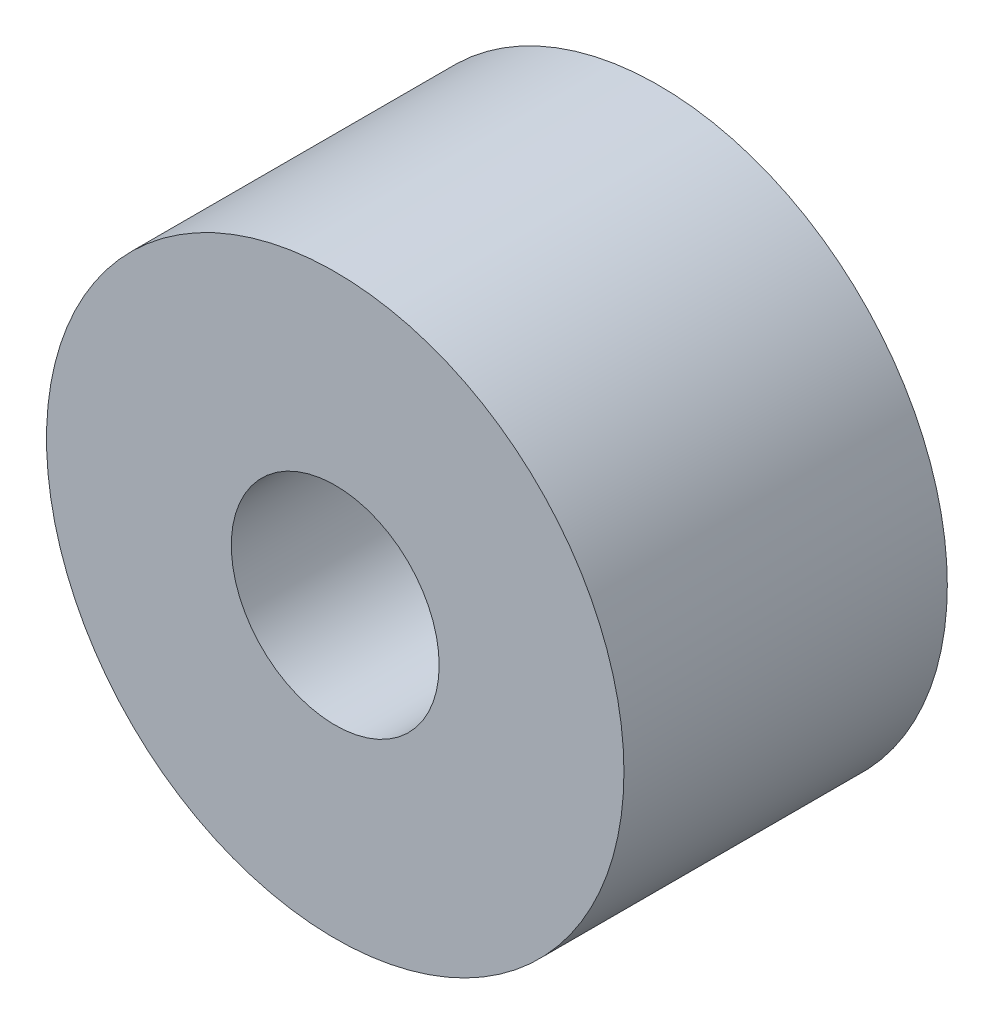
SolidWorks part; units mm, degrees
ref_plane "Plano frontal" through (0, 0, 0) normal (0, 0, 1) x (1, 0, 0)
ref_plane "Plano superior" through (0, 0, 0) normal (0, 1, 0) x (1, 0, 0)
ref_plane "Plano direito" through (0, 0, 0) normal (1, 0, 0) x (0, 0, -1)
sketch "Esboço1" plane through (0, 0, 0) normal (0, 0, 1) x (1, 0, 0)
  circle A0 centre (0, 0) radius 12.5
  circle A1 centre (0, 0) radius 4.5
  dimension "D1" = 9
  dimension "D2" = 25
extrude "Ressalto-extrusão1" add sketch "Esboço1" along normal blind 14
